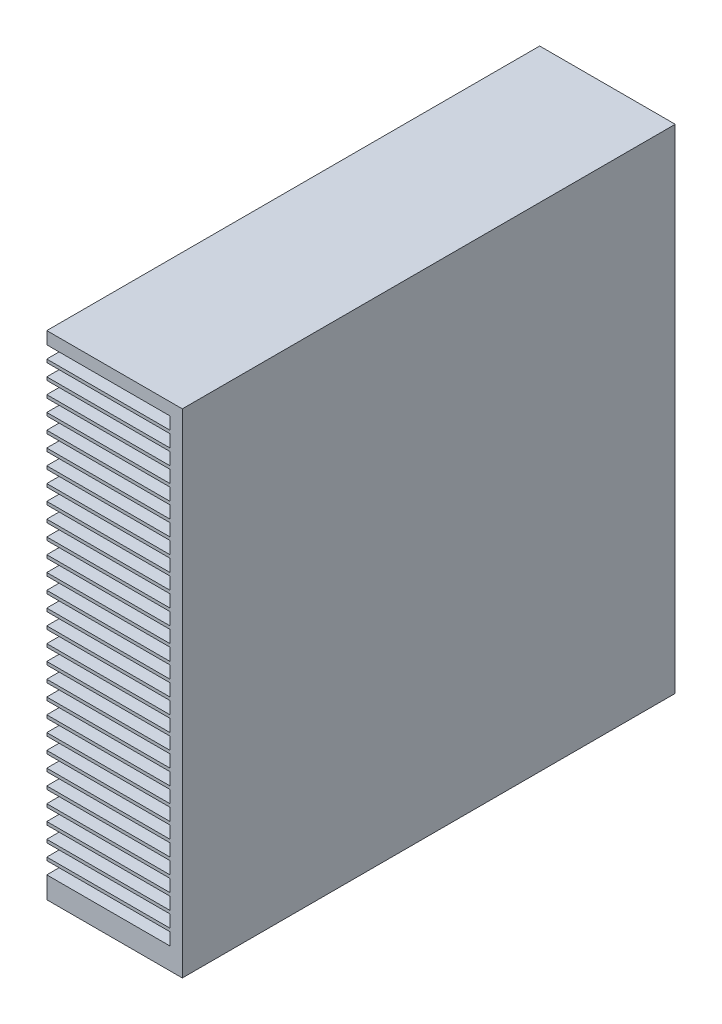
SolidWorks part; units mm, degrees
ref_plane "Front Plane" through (0, 0, 0) normal (0, 0, 1) x (1, 0, 0)
ref_plane "Top Plane" through (0, 0, 0) normal (0, 1, 0) x (1, 0, 0)
ref_plane "Right Plane" through (0, 0, 0) normal (1, 0, 0) x (0, 0, -1)
sketch "Sketch1" plane through (0, 0, 0) normal (0, 0, 1) x (1, 0, 0)
  line L1 (-5.5, -20) -> (5.5, -20)
  line L2 (-5.5, -20) -> (-5.5, 20)
  line L3 (-5.5, 20) -> (5.5, 20)
  line L4 (5.5, -20) -> (5.5, 20)
  line L5 (-5.5, -20) -> (5.5, 20) construction
  line L6 (-5.5, 20) -> (5.5, -20) construction
  point P0 (0, 0)
  dimension "D1" = 11
  dimension "D2" = 40
extrude "Boss-Extrude1" add sketch "Sketch1" along normal mid plane 40
sketch "Sketch2" plane through (0, 0, 20) normal (0, 0, 1) x (1, 0, 0)
  line L0 (-5.5, 19) -> (4.5, 19)
  line L1 (-5.5, 20) -> (-5.5, -20) construction
  line L2 (5.5, 20) -> (-5.5, 20) construction
  line L3 (5.5, -20) -> (5.5, 20) construction
  line L4 (4.5, 19) -> (4.5, 18)
  line L5 (4.5, 18) -> (-5.5, 18)
  line L6 (-5.5, 18) -> (-5.5, 19)
  line L7 (-5.5, 16.75) -> (-5.5, 17.75)
  line L8 (-5.5, 17.75) -> (4.5, 17.75)
  line L9 (4.5, 17.75) -> (4.5, 16.75)
  line L10 (4.5, 16.75) -> (-5.5, 16.75)
  line L11 (-5.5, 15.5) -> (-5.5, 16.5)
  line L12 (-5.5, 16.5) -> (4.5, 16.5)
  line L13 (4.5, 16.5) -> (4.5, 15.5)
  line L14 (4.5, 15.5) -> (-5.5, 15.5)
  line L15 (-5.5, 14.25) -> (-5.5, 15.25)
  line L16 (-5.5, 15.25) -> (4.5, 15.25)
  line L17 (4.5, 15.25) -> (4.5, 14.25)
  line L18 (4.5, 14.25) -> (-5.5, 14.25)
  line L19 (-5.5, 13) -> (-5.5, 14)
  line L20 (-5.5, 14) -> (4.5, 14)
  line L21 (4.5, 14) -> (4.5, 13)
  line L22 (4.5, 13) -> (-5.5, 13)
  line L23 (-5.5, 11.75) -> (-5.5, 12.75)
  line L24 (-5.5, 12.75) -> (4.5, 12.75)
  line L25 (4.5, 12.75) -> (4.5, 11.75)
  line L26 (4.5, 11.75) -> (-5.5, 11.75)
  line L27 (-5.5, 10.5) -> (-5.5, 11.5)
  line L28 (-5.5, 11.5) -> (4.5, 11.5)
  line L29 (4.5, 11.5) -> (4.5, 10.5)
  line L30 (4.5, 10.5) -> (-5.5, 10.5)
  line L31 (-5.5, 9.25) -> (-5.5, 10.25)
  line L32 (-5.5, 10.25) -> (4.5, 10.25)
  line L33 (4.5, 10.25) -> (4.5, 9.25)
  line L34 (4.5, 9.25) -> (-5.5, 9.25)
  line L35 (-5.5, 8) -> (-5.5, 9)
  line L36 (-5.5, 9) -> (4.5, 9)
  line L37 (4.5, 9) -> (4.5, 8)
  line L38 (4.5, 8) -> (-5.5, 8)
  line L39 (-5.5, 6.75) -> (-5.5, 7.75)
  line L40 (-5.5, 7.75) -> (4.5, 7.75)
  line L41 (4.5, 7.75) -> (4.5, 6.75)
  line L42 (4.5, 6.75) -> (-5.5, 6.75)
  line L43 (-5.5, 5.5) -> (-5.5, 6.5)
  line L44 (-5.5, 6.5) -> (4.5, 6.5)
  line L45 (4.5, 6.5) -> (4.5, 5.5)
  line L46 (4.5, 5.5) -> (-5.5, 5.5)
  line L47 (-5.5, 4.25) -> (-5.5, 5.25)
  line L48 (-5.5, 5.25) -> (4.5, 5.25)
  line L49 (4.5, 5.25) -> (4.5, 4.25)
  line L50 (4.5, 4.25) -> (-5.5, 4.25)
  line L51 (-5.5, 3) -> (-5.5, 4)
  line L52 (-5.5, 4) -> (4.5, 4)
  line L53 (4.5, 4) -> (4.5, 3)
  line L54 (4.5, 3) -> (-5.5, 3)
  line L55 (-5.5, 1.75) -> (-5.5, 2.75)
  line L56 (-5.5, 2.75) -> (4.5, 2.75)
  line L57 (4.5, 2.75) -> (4.5, 1.75)
  line L58 (4.5, 1.75) -> (-5.5, 1.75)
  line L59 (-5.5, 0.5) -> (-5.5, 1.5)
  line L60 (-5.5, 1.5) -> (4.5, 1.5)
  line L61 (4.5, 1.5) -> (4.5, 0.5)
  line L62 (4.5, 0.5) -> (-5.5, 0.5)
  line L63 (-5.5, -0.75) -> (-5.5, 0.25)
  line L64 (-5.5, 0.25) -> (4.5, 0.25)
  line L65 (4.5, 0.25) -> (4.5, -0.75)
  line L66 (4.5, -0.75) -> (-5.5, -0.75)
  line L67 (-5.5, -2) -> (-5.5, -1)
  line L68 (-5.5, -1) -> (4.5, -1)
  line L69 (4.5, -1) -> (4.5, -2)
  line L70 (4.5, -2) -> (-5.5, -2)
  line L71 (-5.5, -3.25) -> (-5.5, -2.25)
  line L72 (-5.5, -2.25) -> (4.5, -2.25)
  line L73 (4.5, -2.25) -> (4.5, -3.25)
  line L74 (4.5, -3.25) -> (-5.5, -3.25)
  line L75 (-5.5, -4.5) -> (-5.5, -3.5)
  line L76 (-5.5, -3.5) -> (4.5, -3.5)
  line L77 (4.5, -3.5) -> (4.5, -4.5)
  line L78 (4.5, -4.5) -> (-5.5, -4.5)
  line L79 (-5.5, -5.75) -> (-5.5, -4.75)
  line L80 (-5.5, -4.75) -> (4.5, -4.75)
  line L81 (4.5, -4.75) -> (4.5, -5.75)
  line L82 (4.5, -5.75) -> (-5.5, -5.75)
  line L83 (-5.5, -7) -> (-5.5, -6)
  line L84 (-5.5, -6) -> (4.5, -6)
  line L85 (4.5, -6) -> (4.5, -7)
  line L86 (4.5, -7) -> (-5.5, -7)
  line L87 (-5.5, -8.25) -> (-5.5, -7.25)
  line L88 (-5.5, -7.25) -> (4.5, -7.25)
  line L89 (4.5, -7.25) -> (4.5, -8.25)
  line L90 (4.5, -8.25) -> (-5.5, -8.25)
  line L91 (-5.5, -9.5) -> (-5.5, -8.5)
  line L92 (-5.5, -8.5) -> (4.5, -8.5)
  line L93 (4.5, -8.5) -> (4.5, -9.5)
  line L94 (4.5, -9.5) -> (-5.5, -9.5)
  line L95 (-5.5, -10.7499) -> (-5.5, -9.7499)
  line L96 (-5.5, -9.7499) -> (4.5, -9.7499)
  line L97 (4.5, -9.7499) -> (4.5, -10.7499)
  line L98 (4.5, -10.7499) -> (-5.5, -10.7499)
  line L99 (-5.5, -11.9999) -> (-5.5, -10.9999)
  line L100 (-5.5, -10.9999) -> (4.5, -10.9999)
  line L101 (4.5, -10.9999) -> (4.5, -11.9999)
  line L102 (4.5, -11.9999) -> (-5.5, -11.9999)
  line L103 (-5.5, -13.2499) -> (-5.5, -12.2499)
  line L104 (-5.5, -12.2499) -> (4.5, -12.2499)
  line L105 (4.5, -12.2499) -> (4.5, -13.2499)
  line L106 (4.5, -13.2499) -> (-5.5, -13.2499)
  line L107 (-5.5, -14.4999) -> (-5.5, -13.4999)
  line L108 (-5.5, -13.4999) -> (4.5, -13.4999)
  line L109 (4.5, -13.4999) -> (4.5, -14.4999)
  line L110 (4.5, -14.4999) -> (-5.5, -14.4999)
  line L111 (-5.5, -15.7499) -> (-5.5, -14.7499)
  line L112 (-5.5, -14.7499) -> (4.5, -14.7499)
  line L113 (4.5, -14.7499) -> (4.5, -15.7499)
  line L114 (4.5, -15.7499) -> (-5.5, -15.7499)
  line L115 (-5.5, -16.9999) -> (-5.5, -15.9999)
  line L116 (-5.5, -15.9999) -> (4.5, -15.9999)
  line L117 (4.5, -15.9999) -> (4.5, -16.9999)
  line L118 (4.5, -16.9999) -> (-5.5, -16.9999)
  line L119 (-5.5, -18.2499) -> (-5.5, -17.2499)
  line L120 (-5.5, -17.2499) -> (4.5, -17.2499)
  line L121 (4.5, -17.2499) -> (4.5, -18.2499)
  line L122 (4.5, -18.2499) -> (-5.5, -18.2499)
  dimension "D1" = 1
  dimension "D2" = 1
  dimension "D3" = 1
  dimension "D4" = 30
extrude "Cut-Extrude2" cut sketch "Sketch2" against normal up to surface (40 mm away) up to face at (0, 0, -20)
